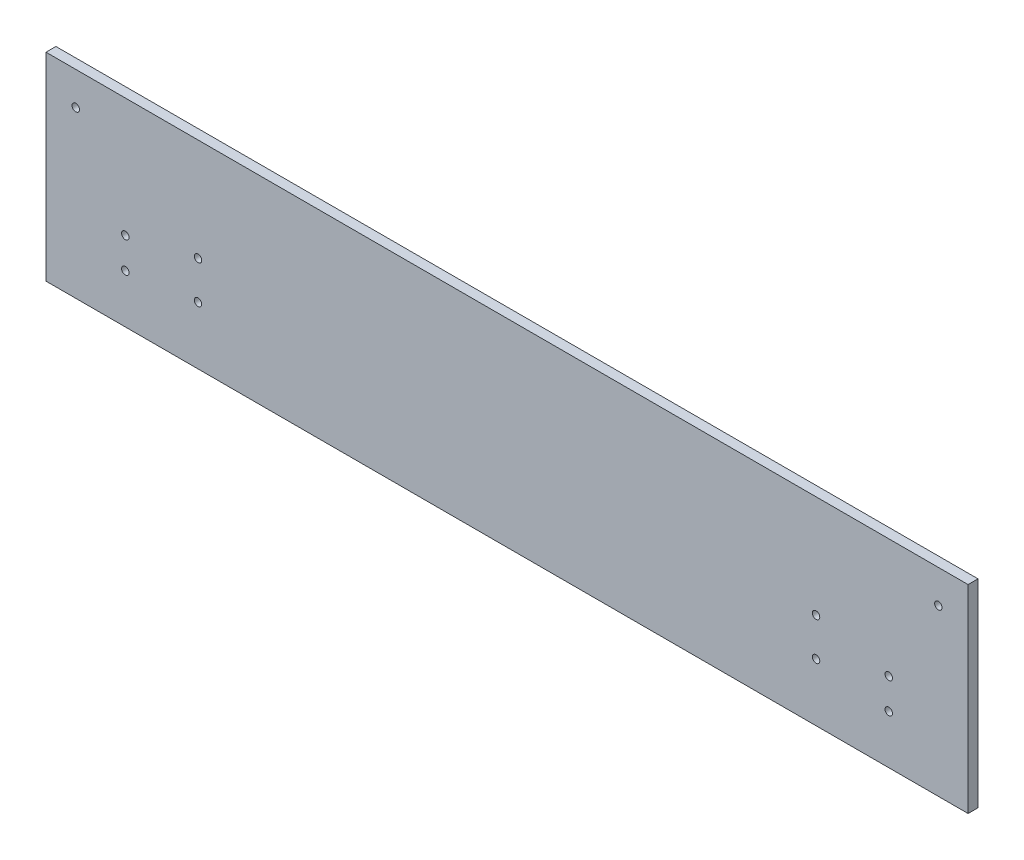
SolidWorks part; units mm, degrees
material "Pino"
ref_plane "Piano frontale" through (0, 0, 0) normal (0, 0, 1) x (1, 0, 0)
ref_plane "Piano superiore" through (0, 0, 0) normal (0, 1, 0) x (1, 0, 0)
ref_plane "Piano destro" through (0, 0, 0) normal (1, 0, 0) x (0, 0, -1)
sketch "Schizzo1" plane through (0, 0, 0) normal (0, 0, 1) x (1, 0, 0)
  line L1 (-279, 60) -> (279, 60)
  line L2 (-279, 60) -> (-279, -60)
  line L3 (-279, -60) -> (279, -60)
  line L4 (279, 60) -> (279, -60)
  line L5 (-279, 60) -> (279, -60) construction
  line L6 (-279, -60) -> (279, 60) construction
  point P4 (0, 0)
  dimension "D1" = 558
  dimension "D2" = 120
extrude "Estrusione-Estrusione1" add sketch "Schizzo1" along normal blind 6
sketch "Schizzo2" plane through (0, 0, 6) normal (0, 0, 1) x (1, 0, 0)
  line L0 (187, -2) -> (187, -25) construction
  line L1 (279, -60) -> (279, 60) construction
  line L2 (-279, -60) -> (279, -60) construction
  line L3 (-187, -25) -> (-187, -2) construction
  line L4 (-279, 60) -> (-279, -60) construction
  circle A0 centre (-231, -12) radius 2.25
  circle A1 centre (-231, -30.5) radius 2.25
  circle A2 centre (231, -12) radius 2.25
  circle A3 centre (231, -30.5) radius 2.25
  circle A5 centre (-261, 40) radius 2.25
  circle A7 centre (261, 40) radius 2.25
  circle A8 centre (187, -25) radius 2.25
  circle A9 centre (187, -2) radius 2.25
  circle A10 centre (-187, -2) radius 2.25
  circle A11 centre (-187, -25) radius 2.25
  point P38 (0, 0)
  dimension "D1" = 4.5
  dimension "D2" = 23
  dimension "D3" = 92
  dimension "D4" = 58
  dimension "D5" = 92
  dimension "D6" = 58
extrude "Taglio-Estrusione1" cut sketch "Schizzo2" against normal blind 10
